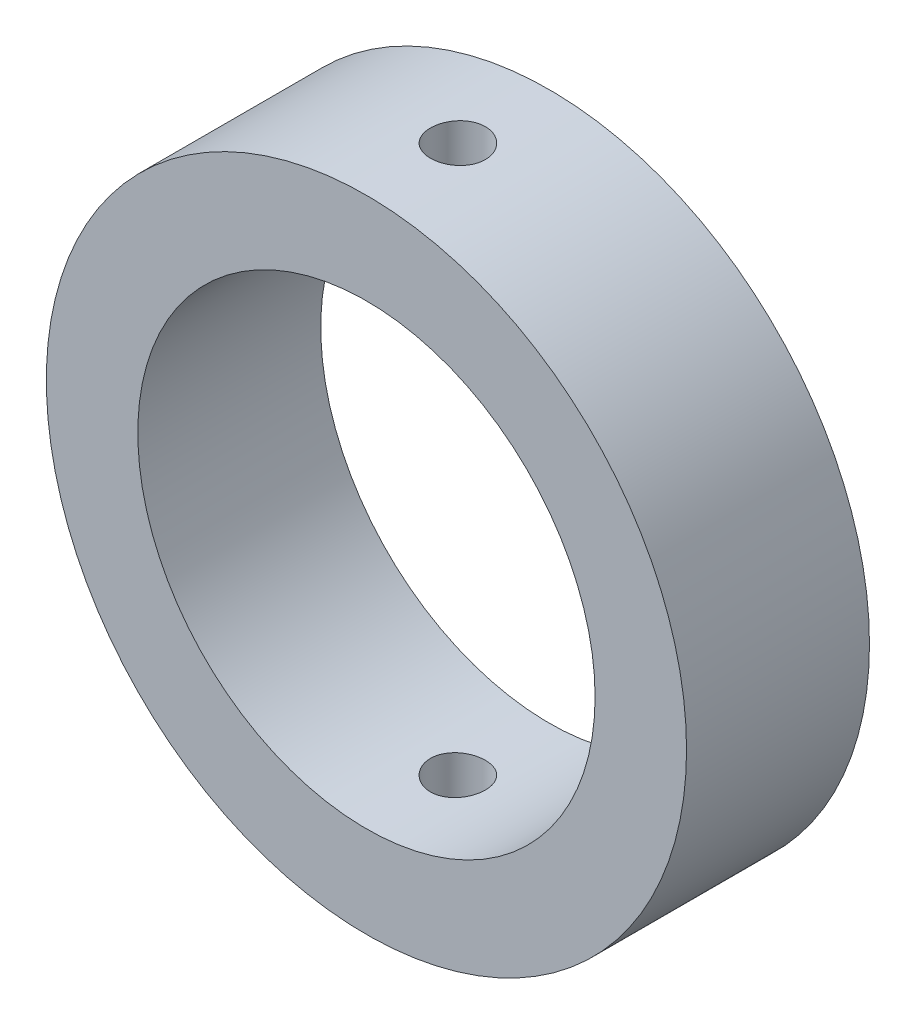
SolidWorks part; units mm, degrees
ref_plane "Front Plane" through (0, 0, 0) normal (0, 0, 1) x (1, 0, 0)
ref_plane "Top Plane" through (0, 0, 0) normal (0, 1, 0) x (1, 0, 0)
ref_plane "Right Plane" through (0, 0, 0) normal (1, 0, 0) x (0, 0, -1)
sketch "Sketch1" plane through (0, 0, 0) normal (0, 0, 1) x (1, 0, 0)
  circle A0 centre (0, 0) radius 25
  circle A1 centre (0, 0) radius 35
  dimension "D1" = 70
  dimension "D2" = 50
extrude "Boss-Extrude2" add sketch "Sketch1" along normal mid plane 20
sketch "Sketch2" plane through (0, 0, 0) normal (0, 1, 0) x (1, 0, 0)
  line L0 (25, 10) -> (-25, 10) construction
  circle A0 centre (0, 0) radius 3
  dimension "D2" = 6
  dimension "D1" = 10
extrude "Cut-Extrude1" cut sketch "Sketch2" against normal through all both and the other way through all
